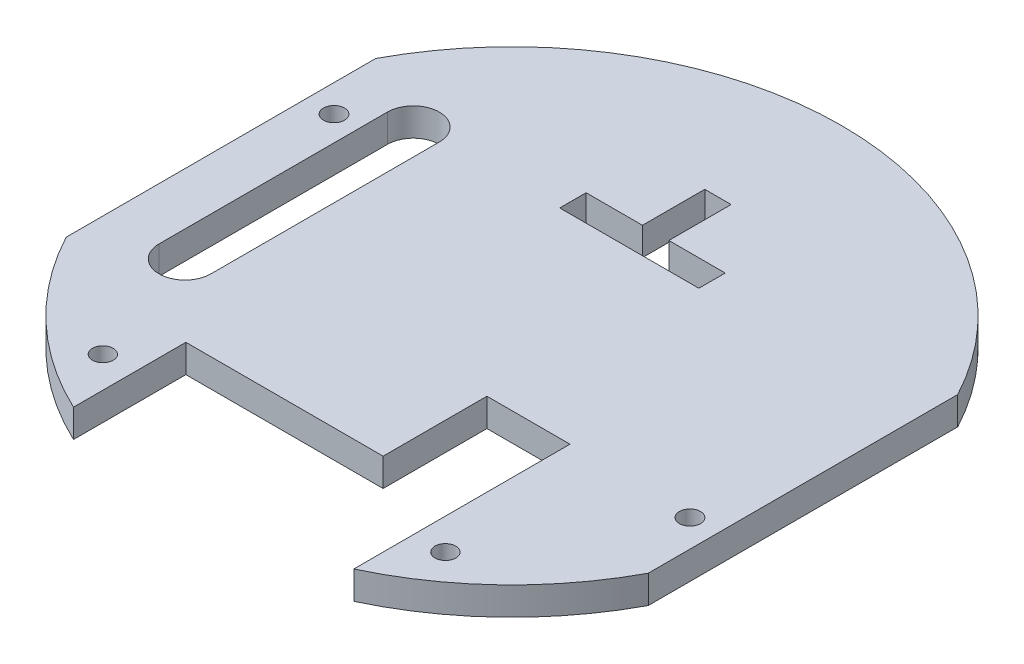
SolidWorks part; units mm, degrees
ref_plane "Front Plane" through (0, 0, 0) normal (0, 0, 1) x (1, 0, 0)
ref_plane "Top Plane" through (0, 0, 0) normal (0, 1, 0) x (1, 0, 0)
ref_plane "Right Plane" through (0, 0, 0) normal (1, 0, 0) x (0, 0, -1)
sketch "Sketch1" plane through (0, 0, 0) normal (0, 1, 0) x (1, 0, 0)
  line L0 (28.0336, 14.9057) -> (28.0336, -14.9057)
  line L1 (-28.0336, 14.9057) -> (-28.0336, -14.9057)
  line L2 (0, 31.75) -> (0, -31.75) construction
  line L4 (6.7, 13.84) -> (-6.7, 13.84)
  line L5 (6.7, 13.84) -> (6.7, 11.3)
  line L6 (6.7, 11.3) -> (-6.7, 11.3)
  line L7 (-6.7, 13.84) -> (-6.7, 11.3)
  arc A0 (-28.0336, -14.9057) -> (28.0336, -14.9057) centre (0, 0) ccw
  arc A1 (28.0336, 14.9057) -> (-28.0336, 14.9057) centre (0, 0) ccw
  dimension "D1" = 63.5
  dimension "D2" = 124
extrude "Base" add sketch "Sketch1" along normal blind 2.7
sketch "Sketch2" plane through (0, 2.7, 0) normal (0, 1, 0) x (-1, 0, 0)
  line L0 (20.5, -11) -> (20.5, 11) construction
  line L1 (18, -11) -> (18, 11)
  line L2 (23, -11) -> (23, 11)
  arc A0 (18, -11) -> (23, -11) centre (20.5, -11) ccw
  arc A1 (23, 11) -> (18, 11) centre (20.5, 11) ccw
  point P2 (20.5, 0)
  dimension "D1" = 22
  dimension "D2" = 18
  dimension "D3" = 5
extrude "Wheel Hole" cut sketch "Sketch2" against normal up to next
sketch "Sketch4" plane through (0, 2.7, 0) normal (0, 1, 0) x (-1, 0, 0)
  line L0 (28.0336, -14.9057) -> (-28.0336, -14.9057) construction
  line L1 (0, 31.75) -> (0, -31.75) construction
  arc A0 (-28.0336, -14.9057) -> (28.0336, -14.9057) centre (0, 0) ccw construction
  arc A1 (28.0336, 14.9057) -> (-28.0336, 14.9057) centre (0, 0) ccw construction
sketch "Sketch9" plane through (0, 2.7, 0) normal (0, 1, 0) x (-1, 0, 0)
  line L0 (0, 0) -> (28.0336, 0) construction
  line L1 (28.0336, -14.9057) -> (28.0336, 14.9057) construction
  line L2 (0, 31.75) -> (0, -31.75) construction
  circle A0 centre (25.4, -8.255) radius 1.016
  circle A1 centre (-25.4, 8.255) radius 1.016
  dimension "D1" = 2.032
  dimension "D2" = 8.255
  dimension "D3" = 25.4
  dimension "D4" = 8.255
  dimension "D5" = 25.4
extrude "Chip Holding" cut sketch "Sketch9" against normal through all
sketch "Sketch10" plane through (0, 0, 0) normal (0, -1, 0) x (1, 0, 0)
  line L0 (6.7, -13.84) -> (-6.7, -13.84) construction
  line L1 (1.27, -13.84) -> (-1.27, -13.84)
  line L2 (1.27, -13.84) -> (1.27, -19.84)
  line L3 (1.27, -19.84) -> (-1.27, -19.84)
  line L4 (-1.27, -13.84) -> (-1.27, -19.84)
  line L5 (0, 31.75) -> (0, -31.75) construction
  point P6 (0, -19.84)
  dimension "D1" = 6
  dimension "D2" = 2.54
extrude "Nub Slot" cut sketch "Sketch10" against normal up to next
sketch "Sketch11" plane through (0, 2.7, 0) normal (0, 1, 0) x (1, 0, 0)
  line L0 (16.5, -22.9137) -> (-16.5, -22.9137) construction
  line L1 (-13.5, -31.75) -> (13.5, -31.75)
  line L2 (-13.5, -31.75) -> (-13.5, -17.9137)
  line L3 (-13.5, -17.9137) -> (5.5, -17.9137)
  line L4 (13.5, -31.75) -> (13.5, -17.9137)
  line L5 (0, -31.75) -> (0, 31.75) construction
  line L12 (13.5, -17.9137) -> (13.5, -7.9137)
  line L13 (13.5, -7.9137) -> (5.5, -7.9137)
  line L14 (5.5, -17.9137) -> (5.5, -7.9137)
  circle A0 centre (16.5, -22.9137) radius 1
  circle A1 centre (-16.5, -22.9137) radius 1
  point P4 (0, -31.75)
  point P7 (0, -22.9137)
  dimension "D1" = 8
  dimension "D2" = 27
  dimension "D3" = 13.8363
  dimension "D4" = 10
  dimension "D5" = 5
extrude "Cut-Extrude1" cut sketch "Sketch11" against normal blind 10
